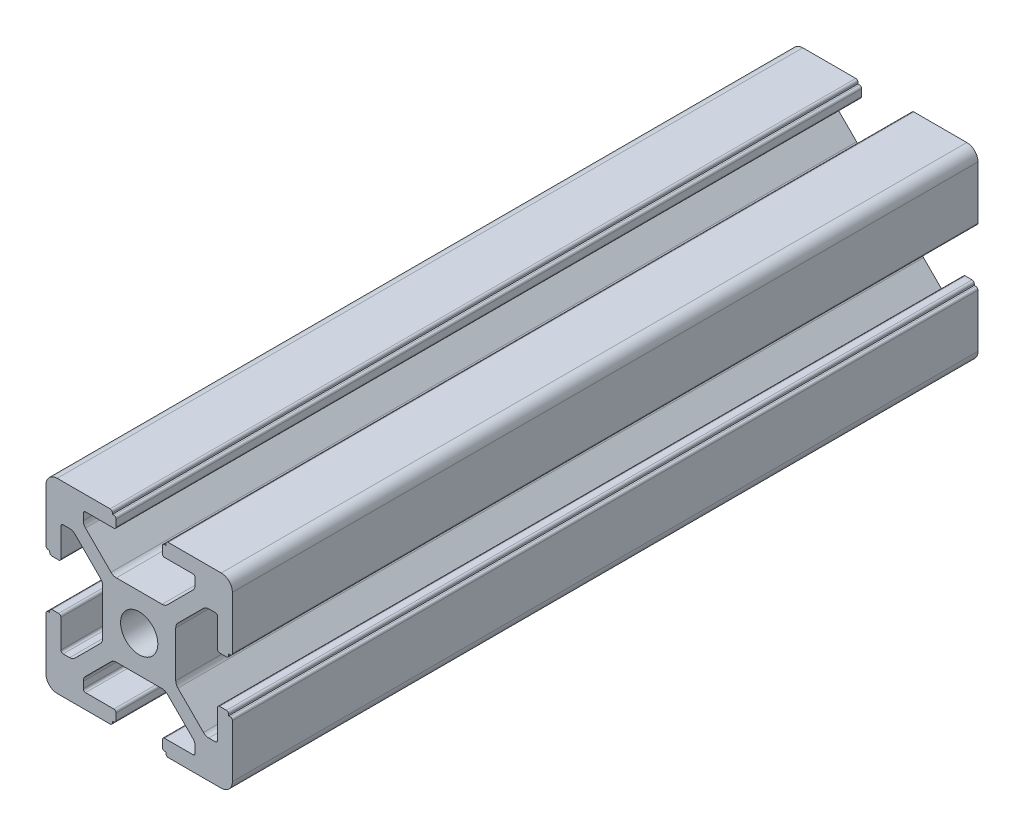
SolidWorks part; units mm, degrees
ref_plane "前视基准面" through (0, 0, 0) normal (0, 0, 1) x (1, 0, 0)
ref_plane "上视基准面" through (0, 0, 0) normal (0, 1, 0) x (1, 0, 0)
ref_plane "右视基准面" through (0, 0, 0) normal (1, 0, 0) x (0, 0, -1)
sketch "草图1" plane through (0, 0, 0) normal (0, 0, 1) x (1, 0, 0)
  line L0 (-11.5808, 11.5745) -> (-11.5808, 4.4745)
  line L1 (-11.2808, 4.1745) -> (-11.0808, 4.1745)
  line L2 (-11.0808, 4.1745) -> (-11.0808, 3.9745)
  line L3 (-10.7808, 3.6745) -> (-9.8808, 3.6745)
  line L4 (-9.5808, 3.9745) -> (-9.5808, 7.7745)
  line L5 (-9.2808, 8.0745) -> (-8.4092, 8.0745)
  line L6 (-7.7021, 7.7816) -> (-4.2737, 4.3532)
  line L7 (-3.9808, 3.6461) -> (-3.9808, -2.4971)
  line L8 (-4.2737, -3.2042) -> (-7.7021, -6.6326)
  line L9 (-8.4092, -6.9255) -> (-9.2808, -6.9255)
  line L10 (-9.5808, -6.6255) -> (-9.5808, -2.8255)
  line L11 (-9.8808, -2.5255) -> (-10.7808, -2.5255)
  line L12 (-11.0808, -2.8255) -> (-11.0808, -3.0255)
  line L13 (-11.0808, -3.0255) -> (-11.2808, -3.0255)
  line L14 (-11.5808, -3.3255) -> (-11.5808, -10.4255)
  line L15 (-10.0808, -11.9255) -> (-2.9808, -11.9255)
  line L16 (-2.6808, -11.6255) -> (-2.6808, -11.4255)
  line L17 (-2.6808, -11.4255) -> (-2.4808, -11.4255)
  line L18 (-2.1808, -11.1255) -> (-2.1808, -10.2255)
  line L19 (-2.4808, -9.9255) -> (-6.2808, -9.9255)
  line L20 (-6.5808, -9.6255) -> (-6.5808, -8.7539)
  line L21 (-6.2879, -8.0468) -> (-2.8594, -4.6184)
  line L22 (-2.1523, -4.3255) -> (3.9908, -4.3255)
  line L23 (4.6979, -4.6184) -> (8.1263, -8.0468)
  line L24 (8.4192, -8.7539) -> (8.4192, -9.6255)
  line L25 (8.1192, -9.9255) -> (4.3192, -9.9255)
  line L26 (4.0192, -10.2255) -> (4.0192, -11.1255)
  line L27 (4.3192, -11.4255) -> (4.5192, -11.4255)
  line L28 (4.5192, -11.4255) -> (4.5192, -11.6255)
  line L29 (4.8192, -11.9255) -> (11.9192, -11.9255)
  line L30 (13.4192, -10.4255) -> (13.4192, -3.3255)
  line L31 (13.1192, -3.0255) -> (12.9192, -3.0255)
  line L32 (12.9192, -3.0255) -> (12.9192, -2.8255)
  line L33 (12.6192, -2.5255) -> (11.7192, -2.5255)
  line L34 (11.4192, -2.8255) -> (11.4192, -6.6255)
  line L35 (11.1192, -6.9255) -> (10.2477, -6.9255)
  line L36 (9.5406, -6.6326) -> (6.1121, -3.2042)
  line L37 (5.8192, -2.4971) -> (5.8192, 3.6461)
  line L38 (6.1121, 4.3532) -> (9.5406, 7.7816)
  line L39 (10.2477, 8.0745) -> (11.1192, 8.0745)
  line L40 (11.4192, 7.7745) -> (11.4192, 3.9745)
  line L41 (11.7192, 3.6745) -> (12.6192, 3.6745)
  line L42 (12.9192, 3.9745) -> (12.9192, 4.1745)
  line L43 (12.9192, 4.1745) -> (13.1192, 4.1745)
  line L44 (13.4192, 4.4745) -> (13.4192, 11.5745)
  line L45 (11.9192, 13.0745) -> (4.8192, 13.0745)
  line L46 (4.5192, 12.7745) -> (4.5192, 12.5745)
  line L47 (4.5192, 12.5745) -> (4.3192, 12.5745)
  line L48 (4.0192, 12.2745) -> (4.0192, 11.3745)
  line L49 (4.3192, 11.0745) -> (8.1192, 11.0745)
  line L50 (8.4192, 10.7745) -> (8.4192, 9.9029)
  line L51 (8.1263, 9.1958) -> (4.6979, 5.7674)
  line L52 (3.9908, 5.4745) -> (-2.1523, 5.4745)
  line L53 (-2.8594, 5.7674) -> (-6.2879, 9.1958)
  line L54 (-6.5808, 9.9029) -> (-6.5808, 10.7745)
  line L55 (-6.2808, 11.0745) -> (-2.4808, 11.0745)
  line L56 (-2.1808, 11.3745) -> (-2.1808, 12.2745)
  line L57 (-2.4808, 12.5745) -> (-2.6808, 12.5745)
  line L58 (-2.6808, 12.5745) -> (-2.6808, 12.7745)
  line L59 (-2.9808, 13.0745) -> (-10.0808, 13.0745)
  arc A0 (-10.0808, 13.0745) -> (-11.5808, 11.5745) centre (-10.0808, 11.5745) ccw
  arc A1 (-11.5808, 4.4745) -> (-11.2808, 4.1745) centre (-11.2808, 4.4745) ccw
  arc A2 (-11.0808, 3.9745) -> (-10.7808, 3.6745) centre (-10.7808, 3.9745) ccw
  arc A3 (-9.8808, 3.6745) -> (-9.5808, 3.9745) centre (-9.8808, 3.9745) ccw
  arc A4 (-9.2808, 8.0745) -> (-9.5808, 7.7745) centre (-9.2808, 7.7745) ccw
  arc A5 (-7.7021, 7.7816) -> (-8.4092, 8.0745) centre (-8.4092, 7.0745) ccw
  arc A6 (-3.9808, 3.6461) -> (-4.2737, 4.3532) centre (-4.9808, 3.6461) ccw
  arc A7 (-4.2737, -3.2042) -> (-3.9808, -2.4971) centre (-4.9808, -2.4971) ccw
  arc A8 (-8.4092, -6.9255) -> (-7.7021, -6.6326) centre (-8.4092, -5.9255) ccw
  arc A9 (-9.5808, -6.6255) -> (-9.2808, -6.9255) centre (-9.2808, -6.6255) ccw
  arc A10 (-9.5808, -2.8255) -> (-9.8808, -2.5255) centre (-9.8808, -2.8255) ccw
  arc A11 (-10.7808, -2.5255) -> (-11.0808, -2.8255) centre (-10.7808, -2.8255) ccw
  arc A12 (-11.2808, -3.0255) -> (-11.5808, -3.3255) centre (-11.2808, -3.3255) ccw
  arc A13 (-11.5808, -10.4255) -> (-10.0808, -11.9255) centre (-10.0808, -10.4255) ccw
  arc A14 (-2.9808, -11.9255) -> (-2.6808, -11.6255) centre (-2.9808, -11.6255) ccw
  arc A15 (-2.4808, -11.4255) -> (-2.1808, -11.1255) centre (-2.4808, -11.1255) ccw
  arc A16 (-2.1808, -10.2255) -> (-2.4808, -9.9255) centre (-2.4808, -10.2255) ccw
  arc A17 (-6.5808, -9.6255) -> (-6.2808, -9.9255) centre (-6.2808, -9.6255) ccw
  arc A18 (-6.2879, -8.0468) -> (-6.5808, -8.7539) centre (-5.5808, -8.7539) ccw
  arc A19 (-2.1523, -4.3255) -> (-2.8594, -4.6184) centre (-2.1523, -5.3255) ccw
  arc A20 (4.6979, -4.6184) -> (3.9908, -4.3255) centre (3.9908, -5.3255) ccw
  arc A21 (8.4192, -8.7539) -> (8.1263, -8.0468) centre (7.4192, -8.7539) ccw
  arc A22 (8.1192, -9.9255) -> (8.4192, -9.6255) centre (8.1192, -9.6255) ccw
  arc A23 (4.3192, -9.9255) -> (4.0192, -10.2255) centre (4.3192, -10.2255) ccw
  arc A24 (4.0192, -11.1255) -> (4.3192, -11.4255) centre (4.3192, -11.1255) ccw
  arc A25 (4.5192, -11.6255) -> (4.8192, -11.9255) centre (4.8192, -11.6255) ccw
  arc A26 (11.9192, -11.9255) -> (13.4192, -10.4255) centre (11.9192, -10.4255) ccw
  arc A27 (13.4192, -3.3255) -> (13.1192, -3.0255) centre (13.1192, -3.3255) ccw
  arc A28 (12.9192, -2.8255) -> (12.6192, -2.5255) centre (12.6192, -2.8255) ccw
  arc A29 (11.7192, -2.5255) -> (11.4192, -2.8255) centre (11.7192, -2.8255) ccw
  arc A30 (11.1192, -6.9255) -> (11.4192, -6.6255) centre (11.1192, -6.6255) ccw
  arc A31 (9.5406, -6.6326) -> (10.2477, -6.9255) centre (10.2477, -5.9255) ccw
  arc A32 (5.8192, -2.4971) -> (6.1121, -3.2042) centre (6.8192, -2.4971) ccw
  arc A33 (6.1121, 4.3532) -> (5.8192, 3.6461) centre (6.8192, 3.6461) ccw
  arc A34 (10.2477, 8.0745) -> (9.5406, 7.7816) centre (10.2477, 7.0745) ccw
  arc A35 (11.4192, 7.7745) -> (11.1192, 8.0745) centre (11.1192, 7.7745) ccw
  arc A36 (11.4192, 3.9745) -> (11.7192, 3.6745) centre (11.7192, 3.9745) ccw
  arc A37 (12.6192, 3.6745) -> (12.9192, 3.9745) centre (12.6192, 3.9745) ccw
  arc A38 (13.1192, 4.1745) -> (13.4192, 4.4745) centre (13.1192, 4.4745) ccw
  arc A39 (13.4192, 11.5745) -> (11.9192, 13.0745) centre (11.9192, 11.5745) ccw
  arc A40 (4.8192, 13.0745) -> (4.5192, 12.7745) centre (4.8192, 12.7745) ccw
  arc A41 (4.3192, 12.5745) -> (4.0192, 12.2745) centre (4.3192, 12.2745) ccw
  arc A42 (4.0192, 11.3745) -> (4.3192, 11.0745) centre (4.3192, 11.3745) ccw
  arc A43 (8.4192, 10.7745) -> (8.1192, 11.0745) centre (8.1192, 10.7745) ccw
  arc A44 (8.1263, 9.1958) -> (8.4192, 9.9029) centre (7.4192, 9.9029) ccw
  arc A45 (3.9908, 5.4745) -> (4.6979, 5.7674) centre (3.9908, 6.4745) ccw
  arc A46 (-2.8594, 5.7674) -> (-2.1523, 5.4745) centre (-2.1523, 6.4745) ccw
  arc A47 (-6.5808, 9.9029) -> (-6.2879, 9.1958) centre (-5.5808, 9.9029) ccw
  arc A48 (-6.2808, 11.0745) -> (-6.5808, 10.7745) centre (-6.2808, 10.7745) ccw
  arc A49 (-2.4808, 11.0745) -> (-2.1808, 11.3745) centre (-2.4808, 11.3745) ccw
  arc A50 (-2.1808, 12.2745) -> (-2.4808, 12.5745) centre (-2.4808, 12.2745) ccw
  arc A51 (-2.6808, 12.7745) -> (-2.9808, 13.0745) centre (-2.9808, 12.7745) ccw
  circle A52 centre (0.9192, 0.5745) radius 2.5
extrude "凸台-拉伸1" add sketch "草图1" along normal blind 100
